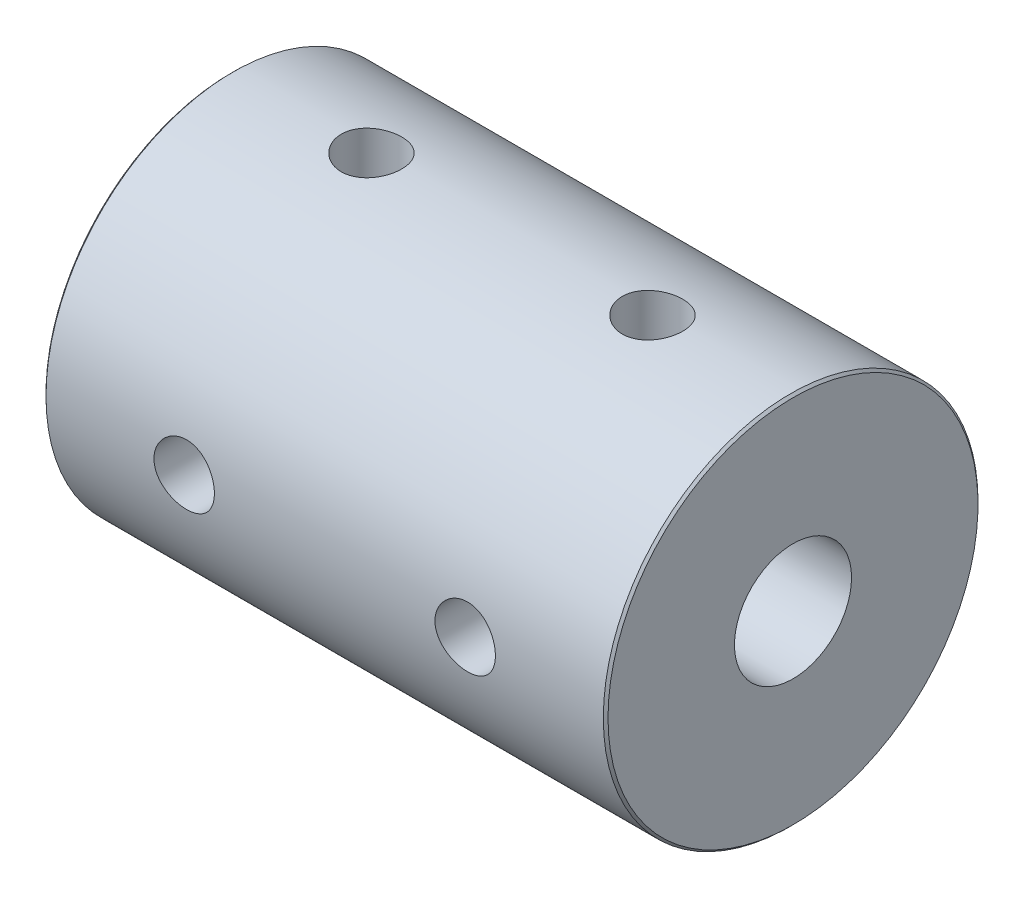
SolidWorks part; units mm, degrees
ref_plane "前视基准面" through (0, 0, 0) normal (0, 0, 1) x (1, 0, 0)
ref_plane "上视基准面" through (0, 0, 0) normal (0, 1, 0) x (1, 0, 0)
ref_plane "右视基准面" through (0, 0, 0) normal (1, 0, 0) x (0, 0, -1)
sketch "草图1" plane through (0, 0, 0) normal (1, 0, 0) x (0, 0, -1)
  circle A0 centre (0, 0) radius 8
  dimension "D1" = 16
extrude "凸台-拉伸1" add sketch "草图1" along normal blind 24
sketch "草图2" plane through (0, 0, 0) normal (-1, 0, 0) x (0, 0, 1)
  circle A0 centre (0, 0) radius 2
  dimension "D1" = 4
extrude "切除-拉伸1" cut sketch "草图2" against normal blind 12
sketch "草图3" plane through (24, 0, 0) normal (1, 0, 0) x (0, 0, -1)
  circle A0 centre (0, 0) radius 2.5
  dimension "D1" = 5
extrude "切除-拉伸2" cut sketch "草图3" against normal blind 12
sketch "草图4" plane through (0, 0, 0) normal (0, 1, 0) x (1, 0, 0)
  line L0 (0, 0) -> (24, 0) construction
  line L1 (24, -8) -> (24, 8) construction
  line L2 (0, 8) -> (0, -8) construction
  circle A0 centre (6, 0) radius 1.29
  circle A1 centre (18, 0) radius 1.29
  dimension "D1" = 2.58
  dimension "D2" = 6
  dimension "D3" = 6
extrude "切除-拉伸3" cut sketch "草图4" along normal up to next
cosmetic thread "装饰螺纹线1" parameters "D2"=3
cosmetic thread "装饰螺纹线2" parameters "D2"=3
sketch "草图5" plane through (0, 0, 0) normal (0, 0, 1) x (1, 0, 0)
  line L0 (0, 0) -> (24, 0) construction
  line L1 (24, -8) -> (24, 8) construction
  line L2 (0, 8) -> (0, -8) construction
  circle A0 centre (18, 0) radius 1.29
  circle A1 centre (6, 0) radius 1.29
  dimension "D1" = 2.58
  dimension "D2" = 6
  dimension "D3" = 6
extrude "切除-拉伸4" cut sketch "草图5" along normal up to next
cosmetic thread "装饰螺纹线3" parameters "D2"=3
cosmetic thread "装饰螺纹线4" parameters "D2"=3
chamfer "倒角1" distance 0.1 angle 45 2 edges at (24, 0, -8) (0, 0, -8)
